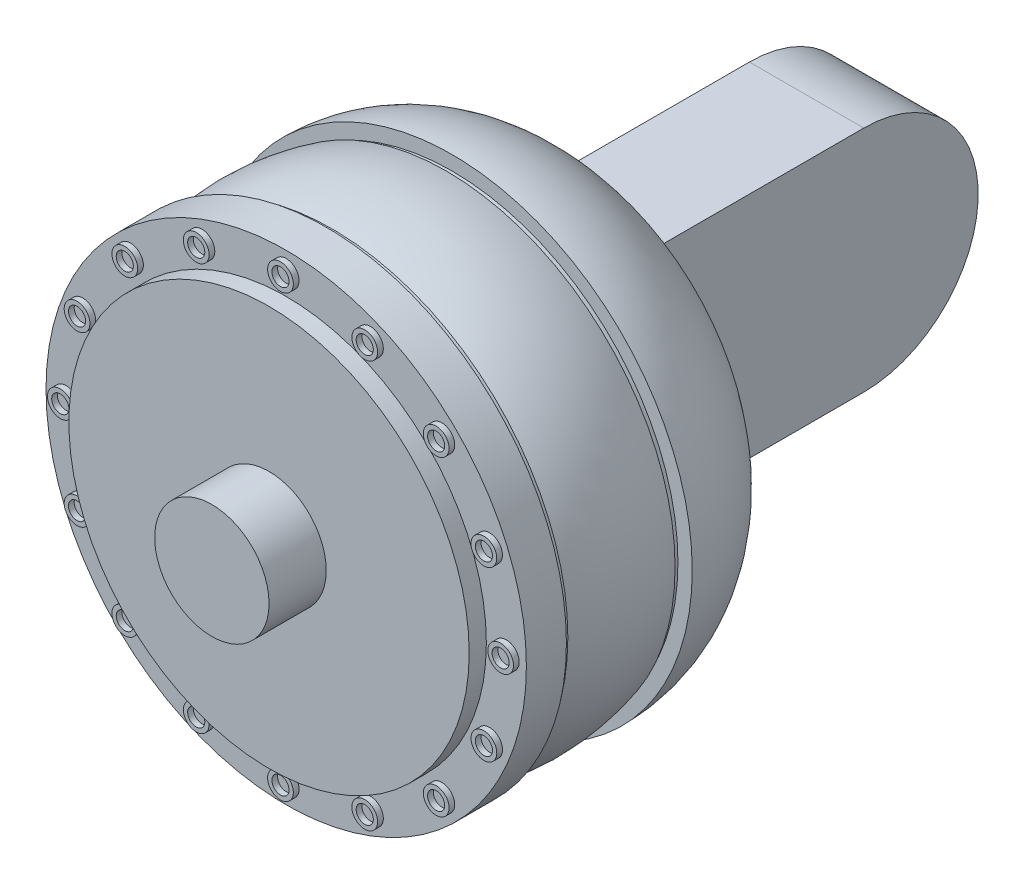
SolidWorks part; units mm, degrees
ref_plane "Front Plane" through (0, 0, 0) normal (0, 0, 1) x (1, 0, 0)
ref_plane "Top Plane" through (0, 0, 0) normal (0, 1, 0) x (1, 0, 0)
ref_plane "Right Plane" through (0, 0, 0) normal (1, 0, 0) x (0, 0, -1)
sketch "Sketch1" plane through (0, 0, 0) normal (0, 1, 0) x (1, 0, 0)
  line L0 (0, 0) -> (0, -20)
  line L1 (0, -20) -> (-42, -20)
  line L2 (-32, 0) -> (0, 0)
  arc A0 (-42, -20) -> (-32, 0) centre (-17, -20) cw
  dimension "D3" = 25
  dimension "D1" = 20
  dimension "D2" = 42
revolve "Revolve1" add sketch "Sketch1" angle 360 about L0
sketch "Sketch2" plane through (0, 0, 20) normal (0, 0, 1) x (1, 0, 0)
  circle A0 centre (0, 0) radius 39.5
  dimension "D1" = 79
extrude "Boss-Extrude1" add sketch "Sketch2" along normal blind 1 contours A0
sketch "Sketch3" plane through (0, 0, 0) normal (0, 1, 0) x (1, 0, 0)
  line L0 (0, -21) -> (-40, -21)
  line L1 (-39.5, -21) -> (39.5, -21) construction
  line L2 (0, -21) -> (0, -41)
  line L3 (0, -41) -> (-40, -41)
  arc A0 (-40, -41) -> (-40, -21) centre (-4.377, -31) cw
  dimension "D3" = 37
  dimension "D1" = 40
  dimension "D2" = 20
revolve "Revolve3" add sketch "Sketch3" angle 360 about L2
sketch "Sketch4" plane through (0, 0, 41) normal (0, 0, 1) x (1, 0, 0)
  circle A0 centre (0, 0) radius 41.25
  dimension "D1" = 82.5
extrude "Boss-Extrude2" add sketch "Sketch4" along normal blind 1
sketch "Sketch5" plane through (0, 0, 42) normal (0, 0, 1) x (1, 0, 0)
  circle A0 centre (0, 0) radius 42
  dimension "D1" = 84
extrude "Boss-Extrude3" add sketch "Sketch5" along normal blind 7
sketch "Sketch6" plane through (0, 0, 49) normal (0, 0, 1) x (1, 0, 0)
  circle A0 centre (0, 0) radius 35
  dimension "D1" = 70
extrude "Boss-Extrude4" add sketch "Sketch6" along normal blind 3
sketch "Sketch7" plane through (0, 0, 49) normal (0, 0, 1) x (1, 0, 0)
  circle A3 centre (38.5, 0) radius 2.25
  circle A4 centre (38.5, 0) radius 1.5
  dimension "D1" = 4.5
  dimension "D2" = 3
extrude "Boss-Extrude5" add sketch "Sketch7" along normal blind 1
pattern_circular "CirPattern1" count 16 over 360 about axis through (0, 0, 0) along (0, 0, 1) of "Boss-Extrude5"
sketch "Sketch8" plane through (0, 0, 0) normal (0, 0, -1) x (-1, 0, 0)
  line L1 (10, -20) -> (-10, -20)
  line L2 (10, -20) -> (10, 20)
  line L3 (10, 20) -> (-10, 20)
  line L4 (-10, -20) -> (-10, 20)
  line L5 (10, -20) -> (-10, 20) construction
  line L6 (10, 20) -> (-10, -20) construction
  point P0 (0, 0)
  dimension "D1" = 40
  dimension "D2" = 20
extrude "Boss-Extrude6" add sketch "Sketch8" along normal blind 42
sketch "Sketch9" plane through (-10, 0, 0) normal (-1, 0, 0) x (0, 0, 1)
  line L0 (-42, -20) -> (-42, 20) construction
  circle A0 centre (-42, 0) radius 20
  dimension "D1" = 40
extrude "Boss-Extrude7" add sketch "Sketch9" against normal up to surface (20 mm away) up to face at (10, 0, -21)
sketch "Sketch10" plane through (-10, 0, 0) normal (-1, 0, 0) x (0, 0, 1)
  circle A0 centre (-42, 0) radius 10
  dimension "D1" = 20
extrude "Boss-Extrude8" add sketch "Sketch10" along normal blind 10
sketch "Sketch11" plane through (0, 0, 52) normal (0, 0, 1) x (1, 0, 0)
  circle A0 centre (0, 0) radius 10
  dimension "D1" = 20
extrude "Boss-Extrude9" add sketch "Sketch11" along normal blind 10
